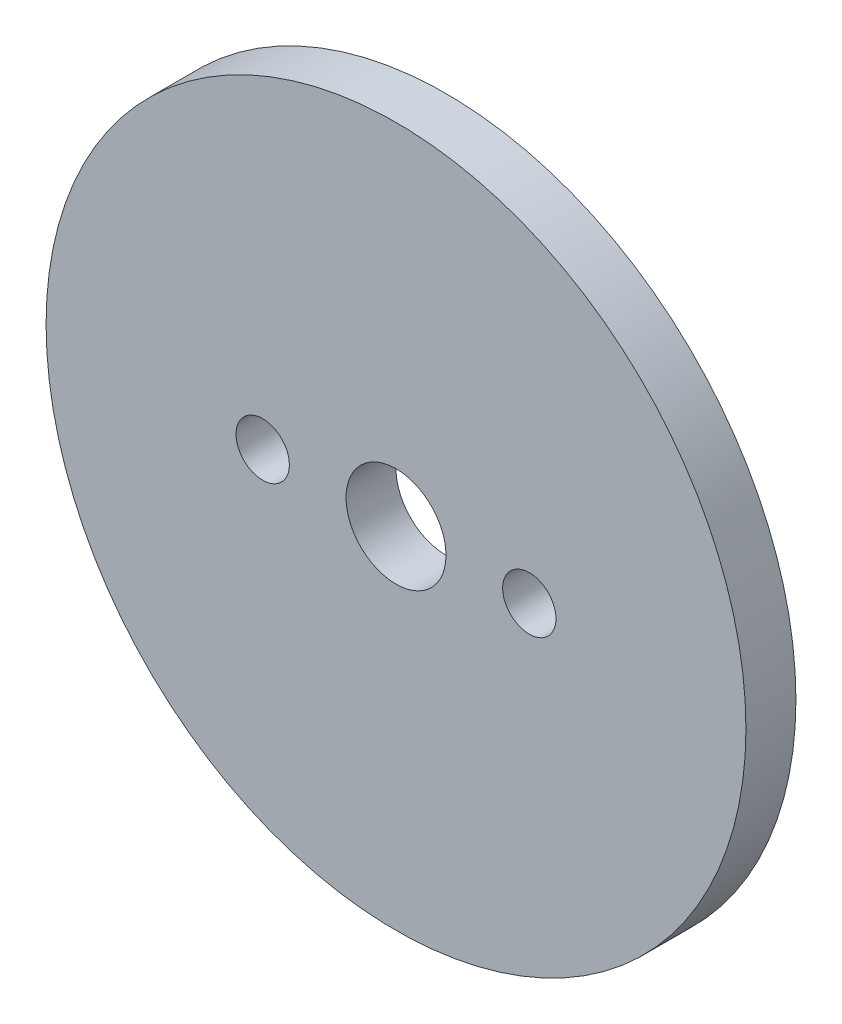
SolidWorks part; units mm, degrees
ref_plane "Plano frontal" through (0, 0, 0) normal (0, 0, 1) x (1, 0, 0)
ref_plane "Plano superior" through (0, 0, 0) normal (0, 1, 0) x (1, 0, 0)
ref_plane "Plano direito" through (0, 0, 0) normal (1, 0, 0) x (0, 0, -1)
sketch "Esboço1" plane through (0, 0, 0) normal (0, 0, 1) x (1, 0, 0)
  line L0 (-8, 0) -> (8, 0) construction
  circle A0 centre (0, 0) radius 21
  circle A1 centre (0, 0) radius 3
  circle A2 centre (-8, 0) radius 1.6
  circle A3 centre (8, 0) radius 1.6
  dimension "D1" = 3.2
  dimension "D2" = 6
  dimension "D4" = 42
  dimension "D3" = 16
extrude "Ressalto-extrusão1" add sketch "Esboço1" along normal mid plane 3
